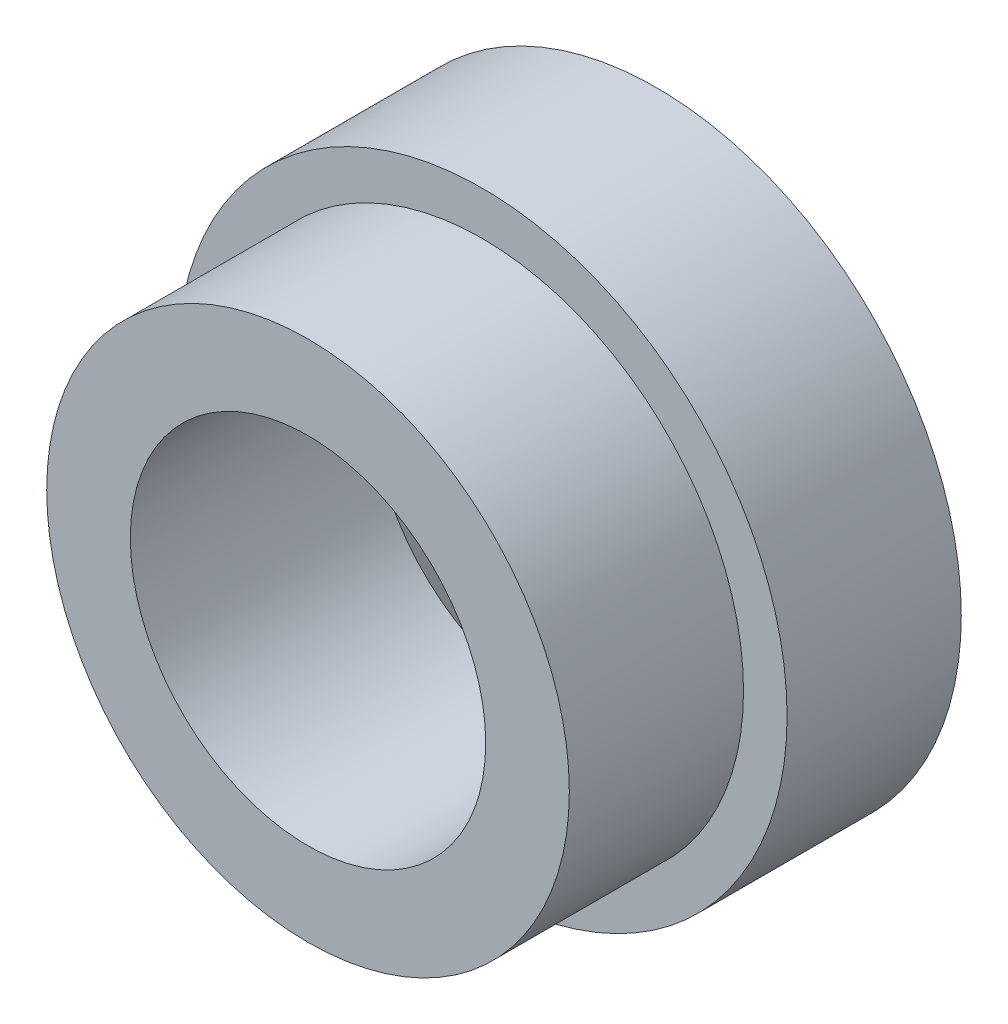
SolidWorks part; units mm, degrees
ref_plane "Front Plane" through (0, 0, 0) normal (0, 0, 1) x (1, 0, 0)
ref_plane "Top Plane" through (0, 0, 0) normal (0, 1, 0) x (1, 0, 0)
ref_plane "Right Plane" through (0, 0, 0) normal (1, 0, 0) x (0, 0, -1)
sketch "Sketch1" plane through (0, 0, 0) normal (0, 0, 1) x (1, 0, 0)
  circle A0 centre (0, 0) radius 5.5563
extrude "Boss-Extrude1" add sketch "Sketch1" along normal blind 3.175
sketch "Sketch2" plane through (0, 0, 3.175) normal (0, 0, 1) x (1, 0, 0)
  circle A0 centre (0, 0) radius 4.7625
extrude "Boss-Extrude2" add sketch "Sketch2" along normal blind 3.175
hole_wizard "CSK for 1/4 Flat Head Machine Screw (100)1" positions "Sketch3" profile "Sketch4" countersink size "1/4" standard "ANSI Inch" end condition up to next
sketch "Sketch3" plane through (0, 0, 0) normal (0, 0, -1) x (-1, 0, 0)
  point P0 (0, 0)
sketch "Sketch4" plane through (0, 0, 0) normal (1, 0, 0) x (0, 1, 0)
  line L0 (0, 0) -> (0, 6.35)
  line L1 (0, 6.35) -> (3.2385, 6.35)
  line L2 (3.2385, 6.35) -> (3.2385, 1.9448)
  line L3 (3.2385, 1.9448) -> (5.5562, 0)
  line L5 (5.5562, 0) -> (0, 0)
  line L6 (-3.2385, 1.9448) -> (-5.5562, 0) construction
  line L11 (0, -6.35) -> (0, 107.95) construction
  dimension "Thru Hole Dia." = 6.477
  dimension "Thru Hole Depth" = 6.35
  dimension "Near C'Sink Dia." = 11.1125
  dimension "Near C'Sink Angle" = 100
